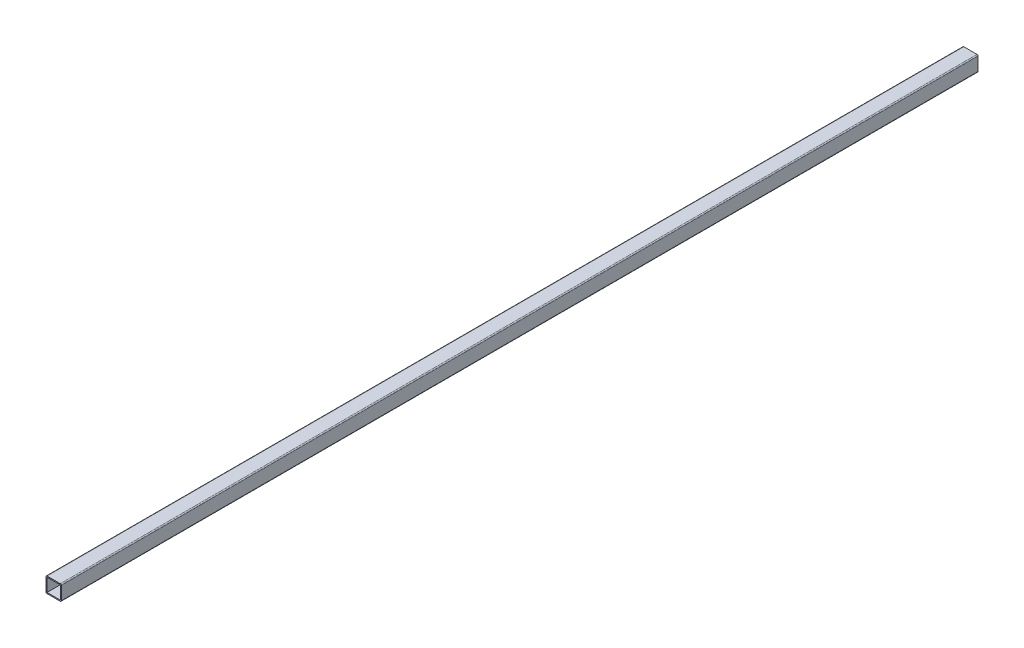
SolidWorks part; units mm, degrees
ref_plane "Front Plane" through (0, 0, 0) normal (0, 0, 1) x (1, 0, 0)
ref_plane "Top Plane" through (0, 0, 0) normal (0, 1, 0) x (1, 0, 0)
ref_plane "Right Plane" through (0, 0, 0) normal (1, 0, 0) x (0, 0, -1)
sketch "Sketch1" plane through (0, 0, 0) normal (0, 0, 1) x (1, 0, 0)
  line L0 (-80.7027, 34.0811) -> (-54.7027, 34.0811)
  line L1 (-82.7027, 36.0811) -> (-52.7027, 36.0811)
  line L2 (-82.7027, 36.0811) -> (-82.7027, 6.0811)
  line L3 (-82.7027, 6.0811) -> (-52.7027, 6.0811)
  line L4 (-52.7027, 36.0811) -> (-52.7027, 6.0811)
  line L5 (-54.7027, 34.0811) -> (-54.7027, 8.0811)
  line L6 (-80.7027, 8.0811) -> (-54.7027, 8.0811)
  line L7 (-80.7027, 34.0811) -> (-80.7027, 8.0811)
  dimension "D1" = 30
  dimension "D2" = 30
  dimension "D3" = 2
extrude "Boss-Extrude1" add sketch "Sketch1" along normal blind 1800
fillet "Fillet1" radius 2 4 edges at (-82.7027, 6.0811, 900) (-52.7027, 6.0811, 900) (-52.7027, 36.0811, 900) (-82.7027, 36.0811, 900)
